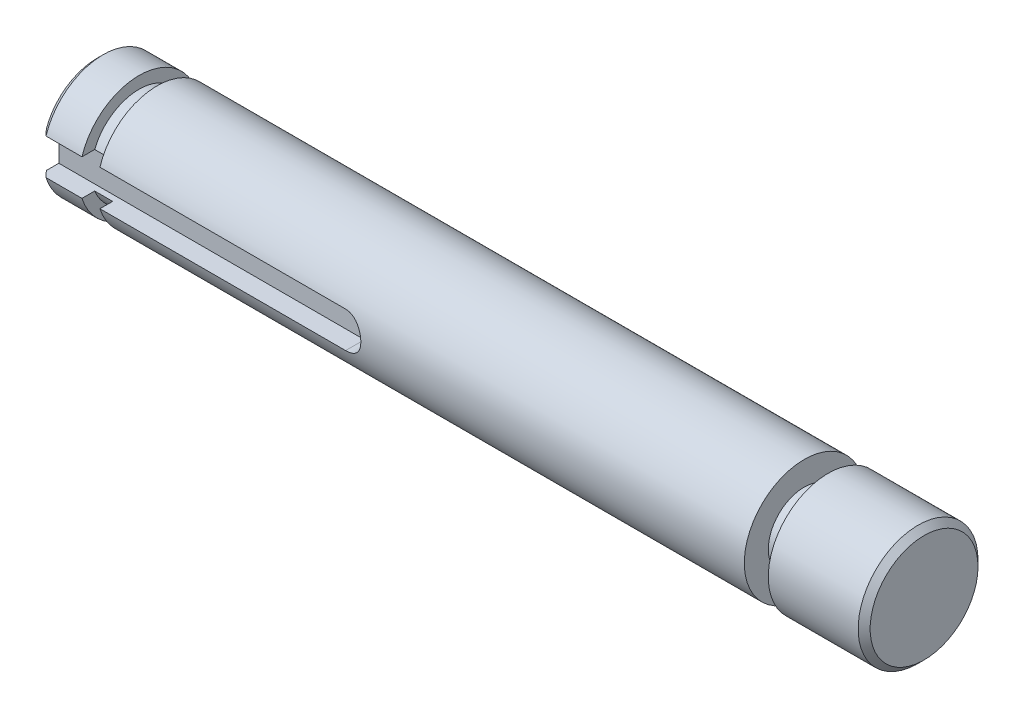
SolidWorks part; units mm, degrees
material "Alloy Steel"
ref_plane "Front Plane" through (0, 0, 0) normal (0, 0, 1) x (1, 0, 0)
ref_plane "Top Plane" through (0, 0, 0) normal (0, 1, 0) x (1, 0, 0)
ref_plane "Right Plane" through (0, 0, 0) normal (1, 0, 0) x (0, 0, -1)
sketch "Sketch1" plane through (0, 0, 0) normal (1, 0, 0) x (0, 0, -1)
  circle A0 centre (0, 0) radius 5
  dimension "D1" = 10
extrude "Boss-Extrude1" add sketch "Sketch1" along normal mid plane 69
sketch "Sketch3" plane through (34.5, 0, 0) normal (1, 0, 0) x (0, 0, -1)
  circle A1 centre (0, 0) radius 5 construction
  circle A2 centre (0, 0) radius 5
  circle A3 centre (0, 0) radius 3
  dimension "D1" = 6
extrude "Cut-Extrude1" cut sketch "Sketch3" along normal blind 2 from offset 10 offset against normal yes
sketch "Sketch4" plane through (-34.5, 0, 0) normal (-1, 0, 0) x (0, 0, 1)
  circle A0 centre (0, 0) radius 5 construction
  circle A1 centre (0, 0) radius 5
  circle A2 centre (0, 0) radius 4
  dimension "D1" = 8
extrude "Cut-Extrude2" cut sketch "Sketch4" along normal blind 1.5 from offset 5 offset against normal yes
chamfer "Chamfer1" distance 0.5 angle 45 2 edges at (-34.5, 0, -5) (34.5, 0, -5)
cosmetic thread "Cosmetic Thread1" parameters "D1"=7, "D2"=6.619
sketch "Sketch5" plane through (0, 0, 0) normal (0, 0, 1) x (1, 0, 0)
  line L0 (-34.5, 1.5) -> (-34.5, -1.5)
  line L1 (-34.5, 4.5) -> (-34.5, -4.5) construction
  line L2 (-34.5, 1.5) -> (-9, 1.5)
  line L3 (-34.5, -1.5) -> (-9, -1.5)
  arc A1 (-9, -1.5) -> (-9, 1.5) centre (-9, 0) ccw
  point P5 (-22.8659, 0)
  dimension "D2" = 1.5
  dimension "D1" = 25.5
  dimension "D3" = 3
  dimension "D4" = 9
  dimension "D5" = 9
extrude "Cut-Extrude3" cut sketch "Sketch5" along normal through all from offset 3.2
